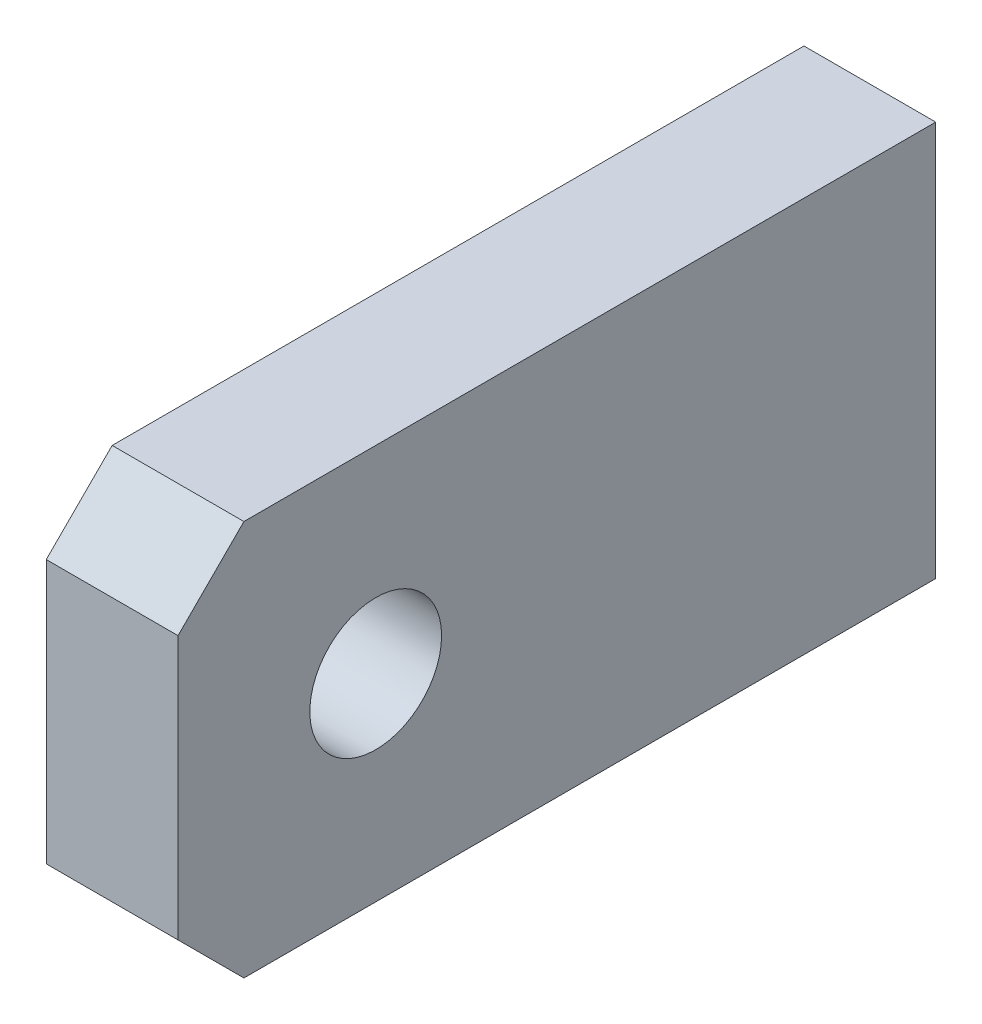
SolidWorks part; units mm, degrees
ref_plane "Front Plane" through (0, 0, 0) normal (0, 0, 1) x (1, 0, 0)
ref_plane "Top Plane" through (0, 0, 0) normal (0, 1, 0) x (1, 0, 0)
ref_plane "Right Plane" through (0, 0, 0) normal (1, 0, 0) x (0, 0, -1)
sketch "Sketch4" plane through (0, 0, 0) normal (1, 0, 0) x (0, 0, -1)
  line L1 (-11.5, -6) -> (11.5, -6)
  line L2 (-11.5, -6) -> (-11.5, 6)
  line L3 (-11.5, 6) -> (11.5, 6)
  line L4 (11.5, -6) -> (11.5, 6)
  line L5 (-11.5, -6) -> (11.5, 6) construction
  line L6 (-11.5, 6) -> (11.5, -6) construction
  point P0 (0, 0)
  dimension "D1" = 23
  dimension "D2" = 12
extrude "Boss-Extrude2" add sketch "Sketch4" against normal blind 4
sketch "Sketch5" plane through (0, 0, -11.5) normal (0, 0, -1) x (-1, 0, 0)
  line L0 (4, 6) -> (0, 6) construction
  line L1 (4, -6) -> (4, 6) construction
  line L2 (4, -6) -> (0, -6) construction
  circle A0 centre (2, -4) radius 1.5
  circle A1 centre (2, 4) radius 1.5
  point P6 (0, 0)
  dimension "D2" = 3
  dimension "D1" = 2
  dimension "D3" = 2
  dimension "D4" = 2
extrude "Cut-Extrude3" cut sketch "Sketch5" against normal blind 10
sketch "Sketch6" plane through (0, 0, 0) normal (1, 0, 0) x (0, 0, -1)
  line L0 (11.5, -6) -> (11.5, 6) construction
  circle A0 centre (-5.5, 0) radius 2
  dimension "D1" = 4
  dimension "D2" = 17
extrude "Cut-Extrude4" cut sketch "Sketch6" against normal through all
chamfer "Chamfer1" distance 2 angle 45 2 edges at (-2, -6, 11.5) (-2, 6, 11.5)
